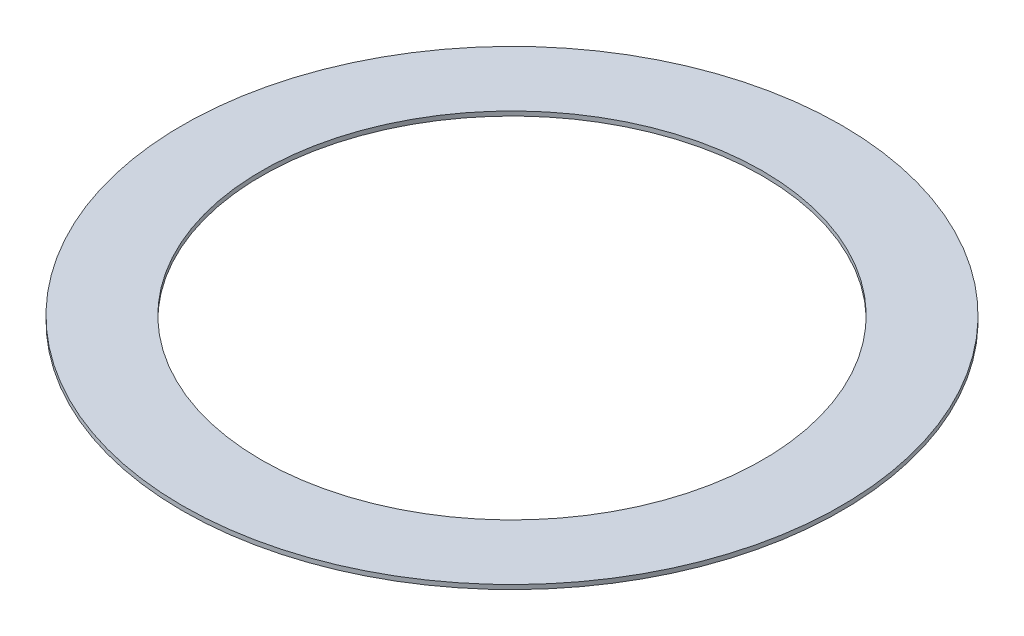
SolidWorks part; units mm, degrees
ref_plane "Front Plane" through (0, 0, 0) normal (0, 0, 1) x (1, 0, 0)
ref_plane "Top Plane" through (0, 0, 0) normal (0, 1, 0) x (1, 0, 0)
ref_plane "Right Plane" through (0, 0, 0) normal (1, 0, 0) x (0, 0, -1)
sketch "Sketch1" plane through (0, 0, 0) normal (0, 1, 0) x (1, 0, 0)
  circle A0 centre (0, 0) radius 75
  circle A1 centre (0, 0) radius 57
  dimension "D1" = 150
  dimension "D2" = 114
extrude "Boss-Extrude1" add sketch "Sketch1" along normal blind 1
